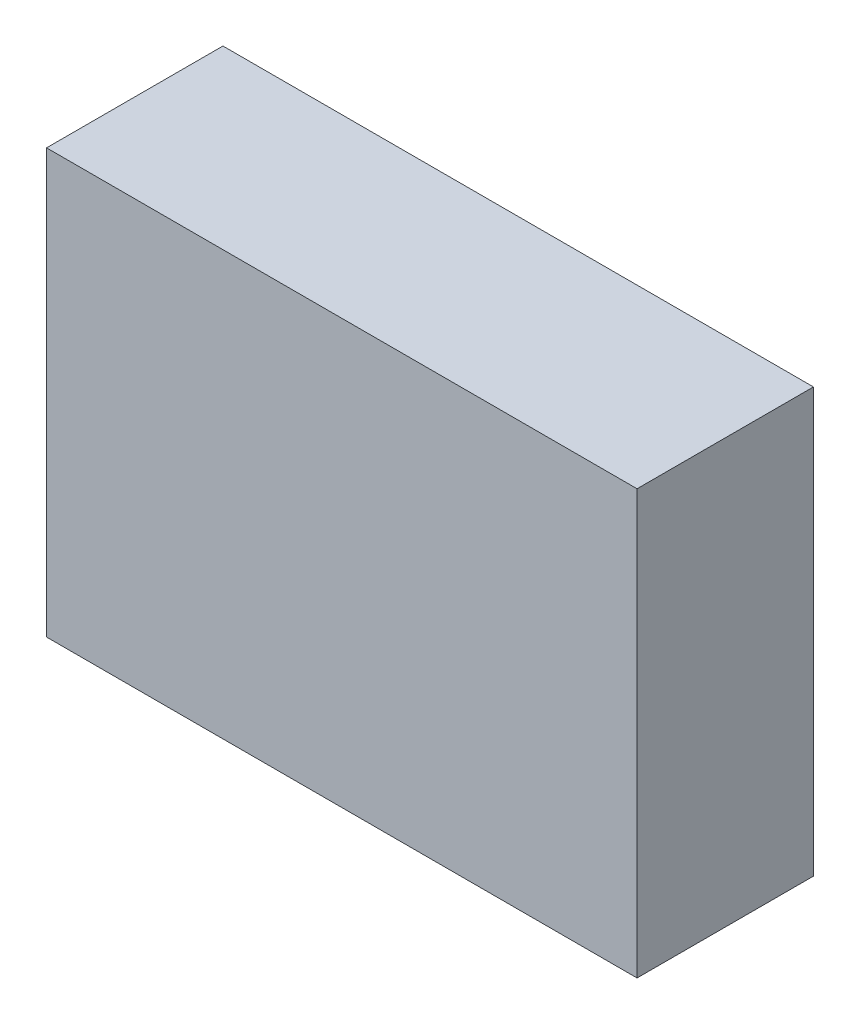
SolidWorks part; units mm, degrees
ref_plane "Front Plane" through (0, 0, 0) normal (0, 0, 1) x (1, 0, 0)
ref_plane "Top Plane" through (0, 0, 0) normal (0, 1, 0) x (1, 0, 0)
ref_plane "Right Plane" through (0, 0, 0) normal (1, 0, 0) x (0, 0, -1)
sketch "Sketch1" plane through (0, 0, 0) normal (0, 0, 1) x (1, 0, 0)
  line L1 (0, 0) -> (30.8, 0)
  line L2 (0, 0) -> (0, 22.1)
  line L3 (0, 22.1) -> (30.8, 22.1)
  line L4 (30.8, 0) -> (30.8, 22.1)
  dimension "D1" = 22.1
  dimension "D2" = 30.8
extrude "Boss-Extrude1" add sketch "Sketch1" along normal blind 9.2
